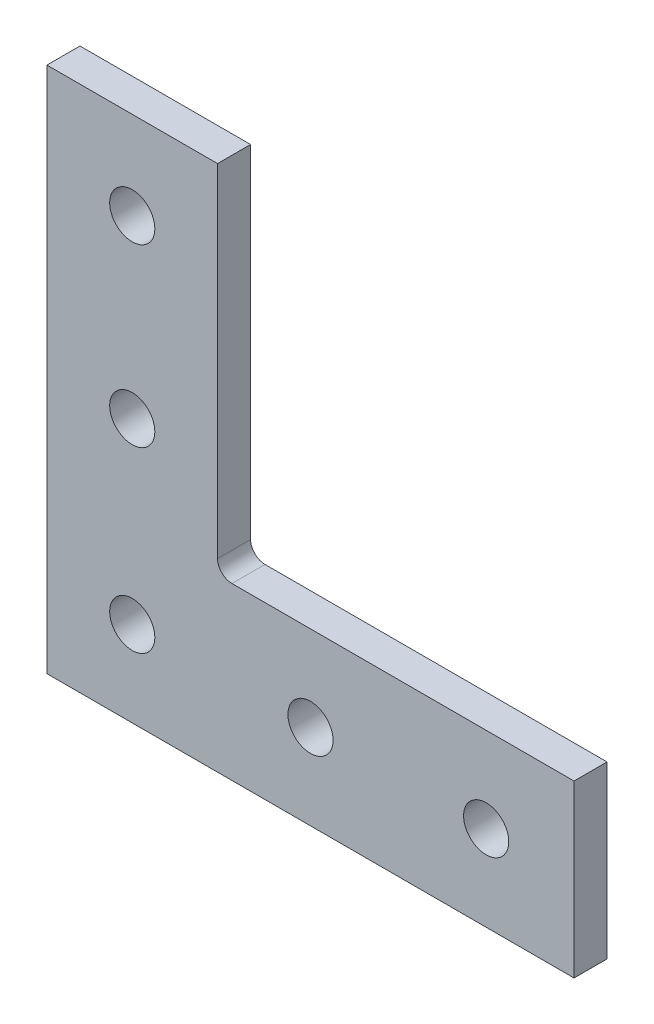
SolidWorks part; units mm, degrees
material "6061 Alloy"
ref_plane "Front Plane" through (0, 0, 0) normal (0, 0, 1) x (1, 0, 0)
ref_plane "Top Plane" through (0, 0, 0) normal (0, 1, 0) x (1, 0, 0)
ref_plane "Right Plane" through (0, 0, 0) normal (1, 0, 0) x (0, 0, -1)
sketch "Sketch1" plane through (0, 0, 0) normal (0, 0, 1) x (1, 0, 0)
  line L0 (-38.1, -38.1) -> (-38.1, 38.1) construction
  line L1 (38.1, -38.1) -> (-38.1, -38.1) construction
  line L2 (-38.1, 38.1) -> (-13.4366, 38.1) construction
  line L3 (-29.0322, 25.4) -> (-22.5044, 25.4) construction
  point P0 (-25.7683, 38.1)
  point P3 (-25.7683, 0)
  point P4 (-38.1, 0)
  point P6 (-38.1, 38.1)
  point P8 (-38.1, 0)
  point P10 (0, 0)
  point P12 (0, -38.1)
  point P14 (-25.7683, 25.4)
  dimension "Length" = 76.2
  dimension "Width" = 24.6634
  dimension "Hole to Edge" = 12.7
  dimension "Hole Spacing" = 25.4
  dimension "Hole Dia" = 6.5278
sketch "Sketch2" plane through (0, 0, 0) normal (1, 0, 0) x (0, 0, -1)
  line L0 (2.3876, 0) -> (-2.3876, 0) construction
  point P4 (0, 0)
  dimension "Thickness" = 4.7752
sketch "Sketch3" plane through (0, 0, 0) normal (0, 0, 1) x (1, 0, 0)
  line L0 (-13.4366, 38.1) -> (-38.1, 38.1)
  line L1 (-38.1, 38.1) -> (-38.1, -38.1)
  line L2 (-38.1, -38.1) -> (38.1, -38.1)
  line L3 (38.1, -38.1) -> (38.1, -13.4366)
  line L4 (38.1, -13.4366) -> (-11.3538, -13.4366)
  line L5 (-13.4366, -11.3538) -> (-13.4366, 38.1)
  arc A0 (-11.3538, -13.4366) -> (-13.4366, -11.3538) centre (-11.3538, -11.3538) cw
  dimension "Radius" = 2.0828
extrude "Boss-Extrude1" add sketch "Sketch3" against normal up to vertex (2.3876 mm away) and the other way up to vertex (2.3876 mm away) up to point (0, 0, -2.3876) other way up to point (0, 0, 2.3876)
sketch "Sketch4" plane through (0, 0, 2.3876) normal (0, 0, 1) x (1, 0, 0)
  line L0 (-29.0322, 25.4) -> (-22.5044, 25.4) construction
  line L1 (-38.1, -38.1) -> (0, 0) construction
  circle A0 centre (-25.7683, 25.4) radius 3.2639
  circle A1 centre (-25.7683, 0) radius 3.2639
  circle A3 centre (0, -25.7683) radius 3.2639
  circle A4 centre (25.4, -25.7683) radius 3.2639
  circle A5 centre (-25.7683, -25.7683) radius 3.2639
extrude "Cut-Extrude1" cut sketch "Sketch4" against normal through all both and the other way through all
ref_plane "Plane1" through (0, -25.7683, 0) normal (0, 1, 0) x (1, 0, 0)
ref_plane "Plane2" through (-25.7683, 0, 0) normal (-1, 0, 0) x (0, 0, 1)
